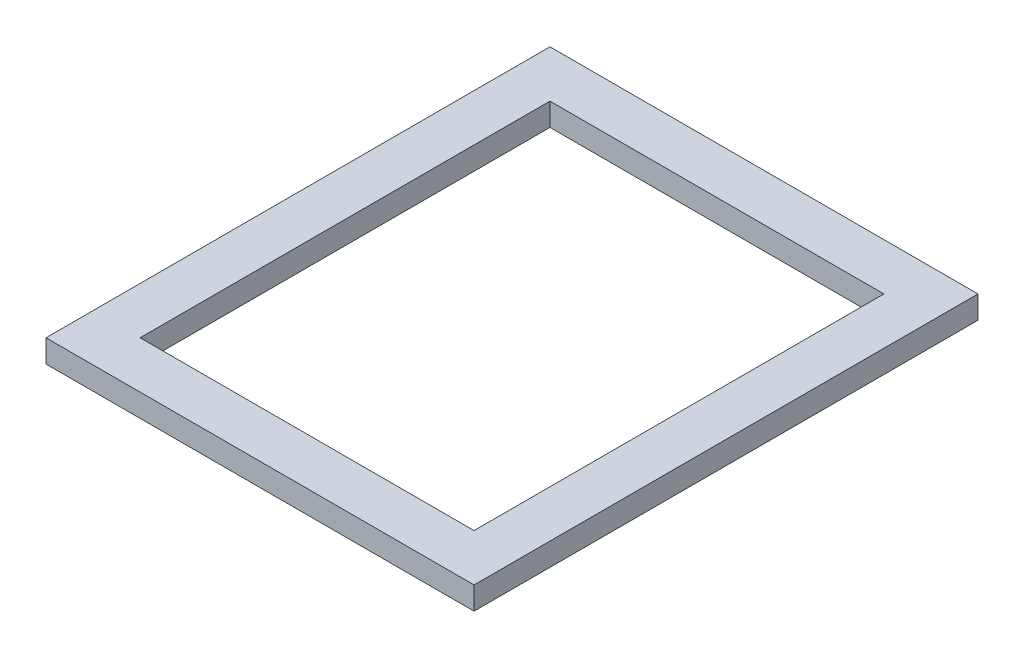
SolidWorks part; units mm, degrees
material "Silicon Rubber"
ref_plane "Front Plane" through (0, 0, 0) normal (0, 0, 1) x (1, 0, 0)
ref_plane "Top Plane" through (0, 0, 0) normal (0, 1, 0) x (1, 0, 0)
ref_plane "Right Plane" through (0, 0, 0) normal (1, 0, 0) x (0, 0, -1)
other "Configuration Table"
sketch "Sketch1" plane through (0, 0, 0) normal (0, 1, 0) x (1, 0, 0)
  line L0 (-14.1, -16.6) -> (14.1, -16.6)
  line L1 (14.1, -16.6) -> (14.1, 16.6)
  line L2 (14.1, 16.6) -> (-14.1, 16.6)
  line L3 (-14.1, 16.6) -> (-14.1, -16.6)
  line L4 (-11, -13.5) -> (11, -13.5)
  line L5 (11, -13.5) -> (11, 13.5)
  line L6 (11, 13.5) -> (-11, 13.5)
  line L7 (-11, 13.5) -> (-11, -13.5)
extrude "Gasket" add sketch "Sketch1" along normal blind 1.5
equation "\"Jar_OD\"= 90  'ASSUMED - Part C fallback - jar outer diameter"
equation "\"Jar_H\"= 120  'ASSUMED - Part C fallback - jar height"
equation "\"Pump_L\"= 45  'ASSUMED - Part C fallback"
equation "\"Pump_W\"= 24  'ASSUMED - Part C fallback"
equation "\"Pump_H\"= 33  'ASSUMED - Part C fallback"
equation "\"Pump_Outlet_OD\"= 7.5  'ASSUMED - Part C fallback"
equation "\"Tube_OD\"= 8  'ASSUMED - Part C fallback"
equation "\"Tube_ID\"= 6  'ASSUMED - Part C fallback"
equation "\"TDS_Body_Dia\"= 12  'ASSUMED - Part C fallback"
equation "\"TDS_Wet_Len\"= 45  'ASSUMED - Part C fallback - length in water"
equation "\"DS_Tube_Dia\"= 6  'ASSUMED - Part C fallback"
equation "\"DS_Tube_Len\"= 50  'ASSUMED - Part C fallback"
equation "\"ORP_Body_Dia\"= 12  'ASSUMED - Part C fallback"
equation "\"ORP_Body_Len\"= 150  'ASSUMED - Part C fallback"
equation "\"ORP_Cap_Dia\"= 16  'ASSUMED - Part C fallback"
equation "\"Turb_W\"= 33  'ASSUMED - Part C fallback - head width"
equation "\"Turb_D\"= 28  'ASSUMED - Part C fallback - head depth"
equation "\"Turb_H\"= 30  'ASSUMED - Part C fallback - head height"
equation "\"Turb_Slot_W\"= 10  'ASSUMED - Part C fallback - slot width"
equation "\"Flow_L\"= 62  'ASSUMED - Part C fallback YF-S201"
equation "\"Flow_W\"= 36  'ASSUMED - Part C fallback"
equation "\"Flow_H\"= 35  'ASSUMED - Part C fallback"
equation "\"Thread_G12_OD\"= 20.955  'ASSUMED - Part C fallback thread G1/2 (major diameter)"
equation "\"Valve_L\"= 75  'ASSUMED - Part C fallback"
equation "\"Valve_W\"= 45  'ASSUMED - Part C fallback"
equation "\"Valve_H\"= 60  'ASSUMED - Part C fallback"
equation "\"Tee_L\"= 40  'ASSUMED - Part C fallback - overall length"
equation "\"Tee_Branch_L\"= 25  'ASSUMED - Part C fallback"
equation "\"Tee_OD\"= 12  'ASSUMED - Part C fallback"
equation "\"Cuv_W\"= 12.5  'ASSUMED - Part C fallback"
equation "\"Cuv_D\"= 12.5  'ASSUMED - Part C fallback"
equation "\"Cuv_H\"= 45  'ASSUMED - Part C fallback"
equation "\"LED_Board_L\"= 20  'ASSUMED - Part C fallback"
equation "\"LED_Board_W\"= 20  'ASSUMED - Part C fallback - LED at centre"
equation "\"GUVA_L\"= 20  'ASSUMED - Part C fallback"
equation "\"GUVA_W\"= 12  'ASSUMED - Part C fallback - sensor at centre"
equation "\"Reed_L\"= 27  'ASSUMED - Part C fallback MC-38 half"
equation "\"Reed_W\"= 14  'ASSUMED - Part C fallback"
equation "\"Reed_H\"= 8  'ASSUMED - Part C fallback"
equation "\"ESP_L\"= 51  'ASSUMED - Part C fallback"
equation "\"ESP_W\"= 28  'ASSUMED - Part C fallback"
equation "\"TFT_L\"= 58  'ASSUMED - Part C fallback - board"
equation "\"TFT_W\"= 35  'ASSUMED - Part C fallback - board"
equation "\"TFT_Win_L\"= 35  'ASSUMED - Part C fallback - visible window"
equation "\"TFT_Win_W\"= 28  'ASSUMED - Part C fallback - visible window"
equation "\"Relay_L\"= 50  'ASSUMED - Part C fallback"
equation "\"Relay_W\"= 26  'ASSUMED - Part C fallback"
equation "\"Relay_H\"= 19  'ASSUMED - Part C fallback"
equation "\"Mosfet_L\"= 34  'ASSUMED - Part C fallback"
equation "\"Mosfet_W\"= 17  'ASSUMED - Part C fallback"
equation "\"Mosfet_H\"= 12  'ASSUMED - Part C fallback"
equation "\"TDS_Board_L\"= 42  'ASSUMED - Part C fallback"
equation "\"TDS_Board_W\"= 32  'ASSUMED - Part C fallback"
equation "\"Turb_Board_L\"= 38  'ASSUMED - Part C fallback"
equation "\"Turb_Board_W\"= 28  'ASSUMED - Part C fallback"
equation "\"BNC_Thread_Dia\"= 9.5  'ASSUMED - Part C fallback"
equation "\"Plate_L\"= 420  'ASSUMED - Part C fallback"
equation "\"Plate_W\"= 297  'ASSUMED - Part C fallback"
equation "\"Plate_T\"= 6  'ASSUMED - Part C fallback"
equation "\"Probe_Clr\"= 0.3  'DESIGN VALUE - Part C rule 3 - printed probe hole = diameter + 0.3"
equation "\"Cuv_Clr\"= 0.2  'DESIGN VALUE - Part C rule 3 - cuvette pocket = size + 0.2"
equation "\"Label_H\"= 0.6  'DESIGN VALUE - Part D - raised label height"
